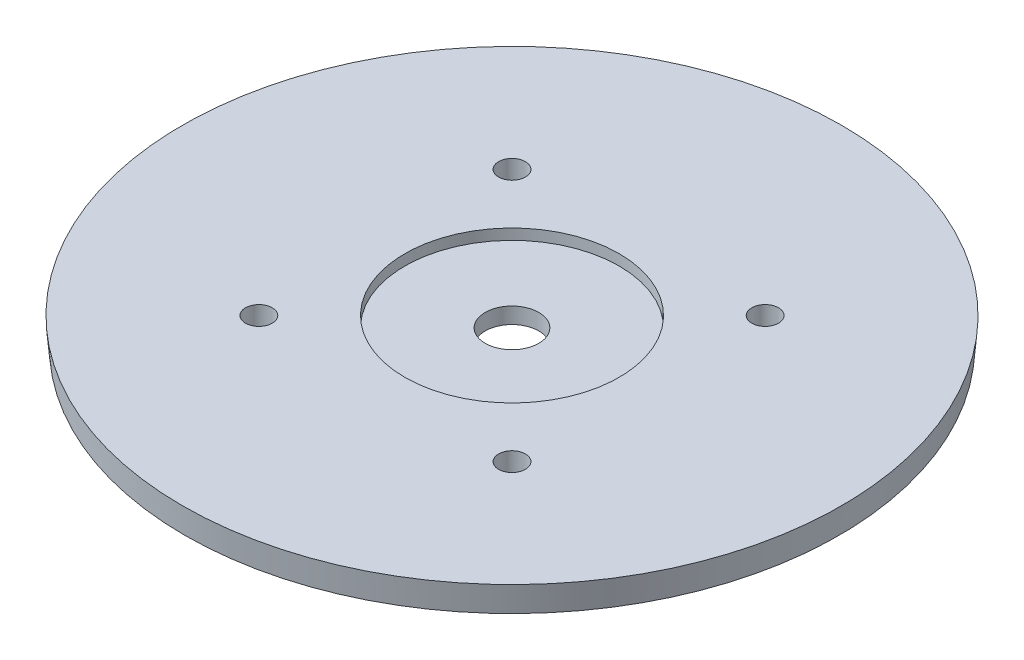
SolidWorks part; units mm, degrees
ref_plane "Front Plane" through (0, 0, 0) normal (0, 0, 1) x (1, 0, 0)
ref_plane "Top Plane" through (0, 0, 0) normal (0, 1, 0) x (1, 0, 0)
ref_plane "Right Plane" through (0, 0, 0) normal (1, 0, 0) x (0, 0, -1)
sketch "Sketch1" plane through (0, 0, 0) normal (0, 1, 0) x (1, 0, 0)
  circle A0 centre (0, 0) radius 61.5
  dimension "D1" = 123
extrude "Boss-Extrude1" add sketch "Sketch1" against normal blind 5 draft 5
sketch "Sketch2" plane through (0, 0, 0) normal (0, 1, 0) x (1, 0, 0)
  circle A0 centre (23.62, 23.62) radius 2.5
  circle A1 centre (23.62, -23.62) radius 2.5
  circle A2 centre (-23.62, -23.62) radius 2.5
  circle A3 centre (-23.62, 23.62) radius 2.5
  circle A4 centre (0, 0) radius 5
  point P0 (0, 0)
  point P12 (0, 0)
  point P13 (0, 0)
extrude "Cut-Extrude2" cut sketch "Sketch2" against normal through all
sketch "Sketch3" plane through (0, 0, 0) normal (0, 1, 0) x (1, 0, 0)
  circle A1 centre (0, 0) radius 20
  dimension "D1" = 40
extrude "Cut-Extrude3" cut sketch "Sketch3" against normal blind 2
